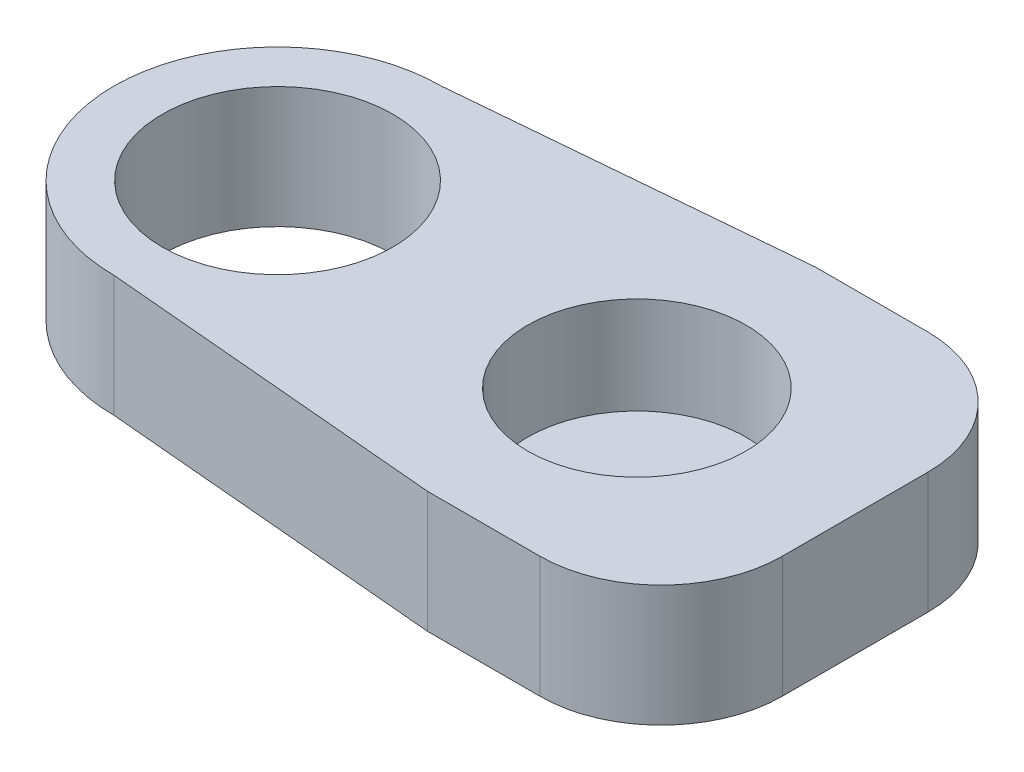
SolidWorks part; units mm, degrees
ref_plane "Piano frontale" through (0, 0, 0) normal (0, 0, 1) x (1, 0, 0)
ref_plane "Piano superiore" through (0, 0, 0) normal (0, 1, 0) x (1, 0, 0)
ref_plane "Piano destro" through (0, 0, 0) normal (1, 0, 0) x (0, 0, -1)
sketch "Sketch1" plane through (0, 0, 0) normal (0, 1, 0) x (1, 0, 0)
  line L3 (5.6491, 8) -> (10.28, 8)
  line L4 (15.28, -3) -> (15.28, 3)
  line L6 (5.6491, -8) -> (-8.53, -6.75)
  line L8 (-8.53, 0) -> (6.28, 0)
  line L11 (-8.53, 4.75) -> (-8.53, 6.75)
  line L12 (5.6491, 8) -> (-8.53, 6.75)
  line L13 (5.6491, -8) -> (10.28, -8)
  circle A0 centre (-8.53, 0) radius 4.75
  arc A5 (15.28, 3) -> (10.28, 8) centre (10.28, 3) ccw
  arc A6 (-8.53, 6.75) -> (-15.28, 0) centre (-8.53, 0) ccw
  arc A7 (-8.53, -6.75) -> (-15.28, 0) centre (-8.53, 0) cw
  arc A8 (15.28, -3) -> (10.28, -8) centre (10.28, -3) cw
  point P0 (0, 0)
  dimension "D3" = 14.81
  dimension "D4" = 5
  dimension "D1" = 6.75
  dimension "D2" = 9.5
  dimension "D5" = 9
extrude "Boss-Extrude1" add sketch "Sketch1" along normal blind 5
sketch "Sketch2" plane through (0, 5, 0) normal (0, 1, 0) x (1, 0, 0)
  line L0 (-8.53, 0) -> (6.28, 0)
  circle A0 centre (6.28, 0) radius 4.5
extrude "Cut-Extrude1" cut sketch "Sketch2" against normal blind 4
